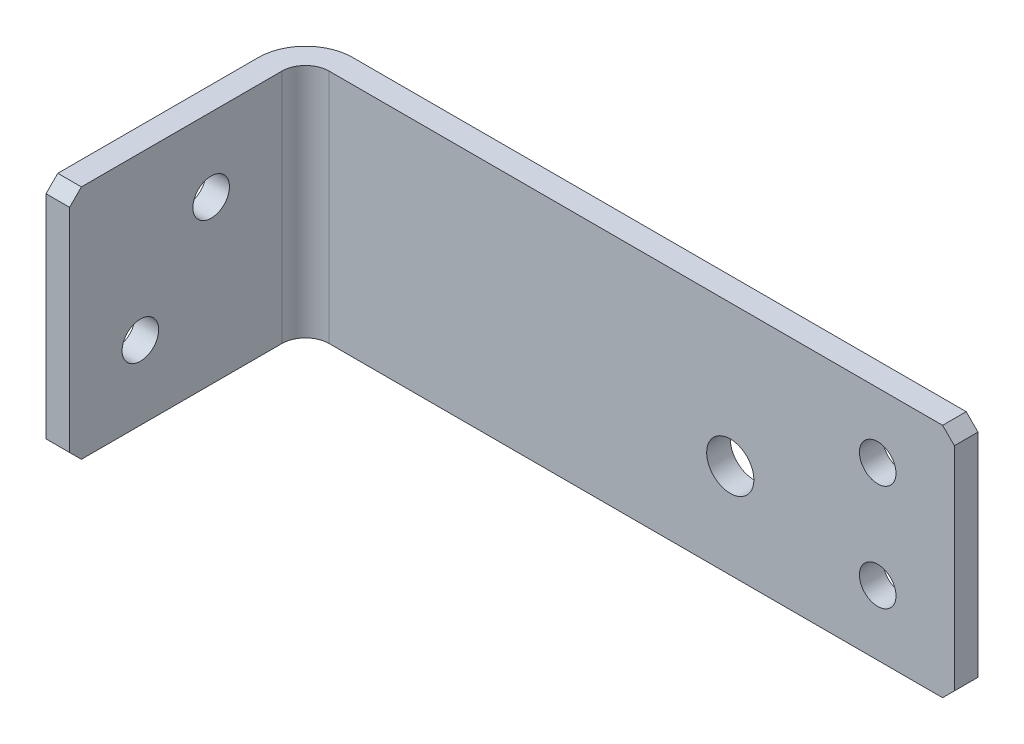
SolidWorks part; units mm, degrees
material "6061 Alloy"
ref_plane "Front Plane" through (0, 0, 0) normal (0, 0, 1) x (1, 0, 0)
ref_plane "Top Plane" through (0, 0, 0) normal (0, 1, 0) x (1, 0, 0)
ref_plane "Right Plane" through (0, 0, 0) normal (1, 0, 0) x (0, 0, -1)
sketch "Sketch1" plane through (0, 0, 0) normal (0, 1, 0) x (1, 0, 0)
  line L0 (0, 0) -> (0, 18)
  line L1 (2, 20) -> (55, 20)
  line L2 (-2, 0) -> (-2, 18)
  line L3 (2, 22) -> (55, 22)
  line L4 (-2, 0) -> (0, 0)
  line L5 (55, 20) -> (55, 22)
  arc A0 (0, 18) -> (2, 20) centre (2, 18) cw
  arc A1 (-2, 18) -> (2, 22) centre (2, 18) cw
  dimension "D1" = 2
  dimension "D2" = 20
  dimension "D3" = 55
  dimension "D4" = 2
extrude "Base" add sketch "Sketch1" along normal blind 20
sketch "Sketch2" plane through (-2, 0, 0) normal (-1, 0, 0) x (0, 0, 1)
  line L0 (0, 20) -> (0, 0) construction
  line L1 (-18, 10) -> (-14.8526, 10) construction
  line L2 (-18, 20) -> (-18, 0) construction
  circle A0 centre (-12, 13.75) radius 1.55
  circle A1 centre (-6, 6.25) radius 1.55
  dimension "D3" = 3.1
  dimension "D1" = 6
  dimension "D2" = 7.5
  dimension "D4" = 6
  dimension "D5" = 3.75
extrude "GuideSideHoles" cut sketch "Sketch2" against normal blind 20
sketch "Sketch3" plane through (0, 0, -22) normal (0, 0, -1) x (-1, 0, 0)
  line L0 (-55, 10) -> (-48.7207, 10) construction
  line L1 (-55, 20) -> (-55, 0) construction
  circle A0 centre (-48.5, 14.5) radius 1.55
  circle A1 centre (-48.5, 5.5) radius 1.55
  dimension "D1" = 9
  dimension "D2" = 3.1
  dimension "D3" = 6.5
extrude "FootSideHoles" cut sketch "Sketch3" against normal through all
chamfer "Chamfer1" distance 1 angle 45
sketch "Sketch4" plane through (0, 0, -22) normal (0, 0, -1) x (-1, 0, 0)
  line L0 (2, 20) -> (2, 0) construction
  line L1 (-54, 0) -> (-2, 0) construction
  circle A0 centre (-36, 8) radius 2
  dimension "D3" = 4
  dimension "D1" = 38
  dimension "D2" = 8
extrude "CableTieHole" cut sketch "Sketch4" against normal through all contours A0
